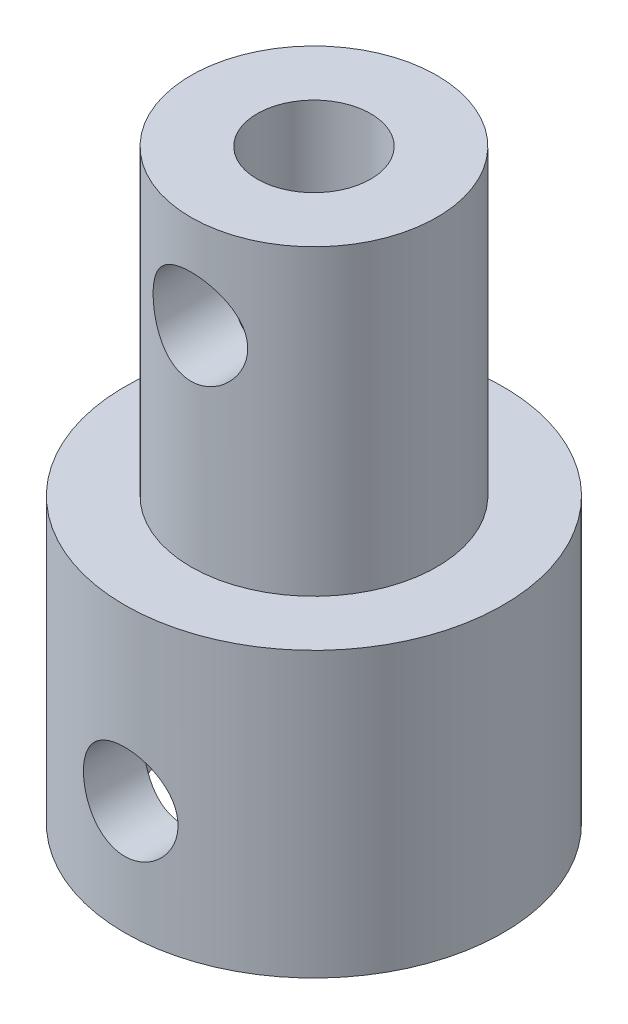
SolidWorks part; units mm, degrees
ref_plane "Plan de face" through (0, 0, 0) normal (0, 0, 1) x (1, 0, 0)
ref_plane "Plan de dessus" through (0, 0, 0) normal (0, 1, 0) x (1, 0, 0)
ref_plane "Plan de droite" through (0, 0, 0) normal (1, 0, 0) x (0, 0, -1)
sketch "Esquisse1" plane through (0, 0, 0) normal (0, 0, 1) x (1, 0, 0)
  line L0 (0, 39.5299) -> (0, -22.7376) construction
  line L2 (-6.5, 31) -> (-3, 31)
  line L3 (-6.5, 31) -> (-6.5, 15)
  line L5 (-3, 31) -> (-3, 0)
  line L6 (-6.5, 15) -> (-10, 15)
  line L8 (-3, 0) -> (-10, 0)
  line L9 (-10, 15) -> (-10, 0)
  point P8 (0, 39.5299)
  point P10 (0, 0)
  dimension "D1" = 3
  dimension "D2" = 15
  dimension "D3" = 16
  dimension "D4" = 10
  dimension "D5" = 6.5
revolve "Révolution1" add sketch "Esquisse1" angle 360 about L0
hole_wizard "Trou taraudé M14x1.51" positions "Esquisse3" profile "Esquisse4" tap size "M14x1.5" standard "ISO"
sketch "Esquisse3" plane through (0, 0, 0) normal (0, -1, 0) x (-1, 0, 0)
  point P0 (0, 0)
sketch "Esquisse4" plane through (0, 0, 0) normal (1, 0, 0) x (0, 0, -1)
  line L0 (0, 0) -> (0, 16.206)
  line L1 (0, 16.206) -> (7, 12)
  line L2 (7, 12) -> (7, 0)
  line L5 (7, 0) -> (0, 0)
  line L10 (0, 16.206) -> (-7, 12) construction
  line L11 (0, -6.35) -> (0, 107.95) construction
  dimension "Diamètre du trou pour taraudage" = 14
  dimension "Profondeur du trou pour taraudage" = 12
  dimension "Angle de pointe" = 118
cosmetic thread "Filetage de perçage1" parameters "D1"=8.5, "D2"=14
hole_wizard "Trou taraudé M61" positions "Esquisse6" profile "Esquisse7" tap size "M6" standard "ISO"
sketch "Esquisse6" plane through (0, 0, 0) normal (0, 0, 1) x (1, 0, 0)
  line L0 (-10, 0) -> (10, 0) construction
  line L1 (3, 31) -> (-3, 31) construction
  point P0 (0, 6)
  point P3 (0, 26)
  point P8 (0, 0)
  point P10 (0, 0)
  point P12 (0, 0)
  dimension "D1" = 6
  dimension "D2" = 5
sketch "Esquisse7" plane through (0, 6, 0) normal (1, 0, 0) x (0, 1, 0)
  line L0 (0, 0) -> (0, 17.5022)
  line L1 (0, 17.5022) -> (2.5, 16)
  line L2 (2.5, 16) -> (2.5, 0)
  line L5 (2.5, 0) -> (0, 0)
  line L10 (0, 17.5022) -> (-2.5, 16) construction
  line L11 (0, -6.35) -> (0, 107.95) construction
  dimension "Diamètre du trou pour taraudage" = 5
  dimension "Profondeur du trou pour taraudage" = 16
  dimension "Angle de pointe" = 118
cosmetic thread "Filetage de perçage2" parameters "D1"=10, "D2"=6
cosmetic thread "Filetage de perçage3" parameters "D1"=6.5, "D2"=6
